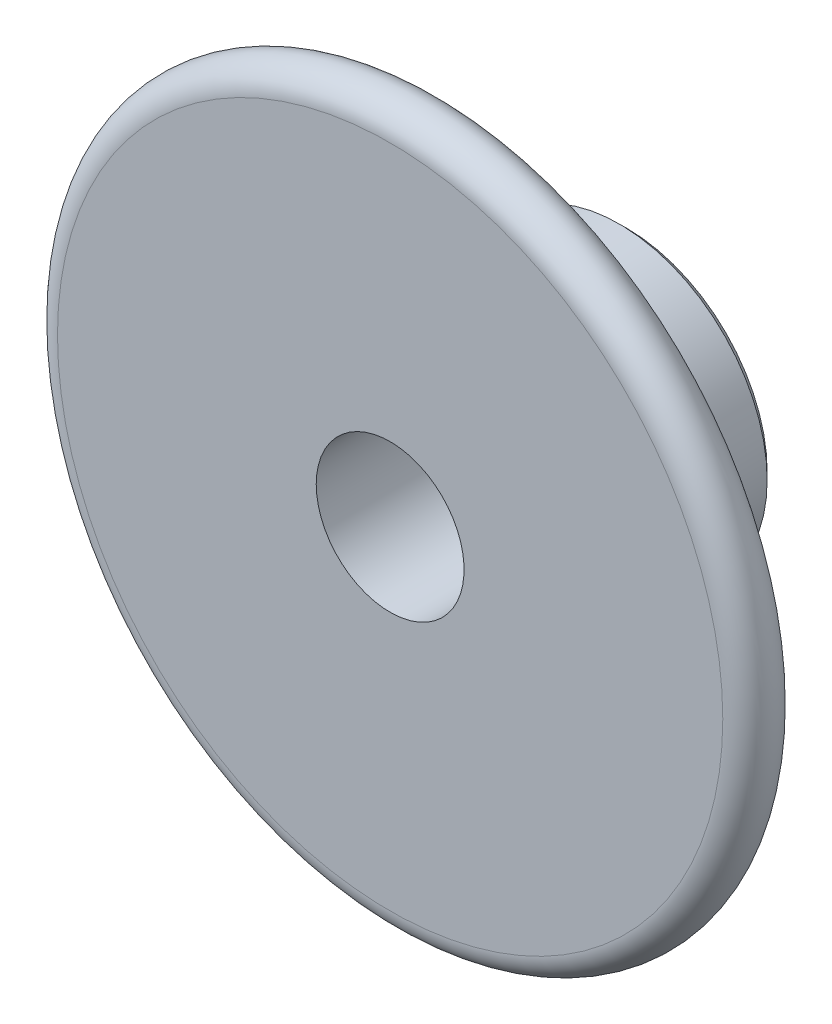
SolidWorks part; units mm, degrees
ref_plane "前视基准面" through (0, 0, 0) normal (0, 0, 1) x (1, 0, 0)
ref_plane "上视基准面" through (0, 0, 0) normal (0, 1, 0) x (1, 0, 0)
ref_plane "右视基准面" through (0, 0, 0) normal (1, 0, 0) x (0, 0, -1)
sketch "草图1" plane through (0, 0, 0) normal (0, 0, 1) x (1, 0, 0)
  circle A0 centre (0, 0) radius 10
  dimension "D1" = 20
extrude "拉伸1" add sketch "草图1" along normal blind 12.5
sketch "草图2" plane through (0, 0, 12.5) normal (0, 0, 1) x (1, 0, 0)
  circle A0 centre (0, 0) radius 22.5
  dimension "D1" = 45
extrude "拉伸2" add sketch "草图2" along normal blind 3.5
sketch "草图3" plane through (0, 0, 0) normal (0, 1, 0) x (1, 0, 0)
  line L0 (-22.5, -12.5) -> (-22.5, -16) construction
  circle A0 centre (-22.5, -14.25) radius 1.75
  dimension "D1" = 3.5
sketch "草图4" plane through (0, 0, 0) normal (0, 0, -1) x (-1, 0, 0)
  circle A0 centre (0, 0) radius 5
  dimension "D1" = 10
extrude "拉伸3" cut sketch "草图4" against normal through all
hole_wizard "M4 螺纹孔1" positions "草图6" profile "草图5" tap size "M4" standard "GB"
sketch "草图6" plane through (0, 0, 0) normal (0, 1, 0) x (1, 0, 0)
  line L0 (10, 0) -> (-10, 0) construction
  point P0 (0, -6)
  dimension "D1" = 6
cosmetic thread "孔螺蚊线1" parameters "D2"=4
sketch "草图5" plane through (0, 0, 6) normal (1, 0, 0) x (0, 0, -1)
  line L0 (0, 0) -> (0, 24.25)
  line L1 (0, 24.25) -> (1.65, 24.25)
  line L2 (1.65, 24.25) -> (1.65, 0)
  line L5 (1.65, 0) -> (0, 0)
  line L11 (0, -6.35) -> (0, 107.95) construction
  dimension "通孔螺纹孔钻头直径" = 3.3
  dimension "通孔螺纹孔钻头深度" = 24.25
chamfer "倒角2" distance 0.5 angle 45 2 edges at (-5, 0, 0) (10, 0, 0)
ref_plane "基准面1" through (0, 0, 13) normal (0, 0, 1) x (1, 0, 0)
revolve "旋转1" add sketch "草图3" angle 360 about axis through (0, 0, 12.5) along (0, 0, -1)
pattern_circular "阵列(圆周)1" count 2 every 90 about axis through (0, 0, 12.5) along (0, 0, -1) of "M4 螺纹孔1"
